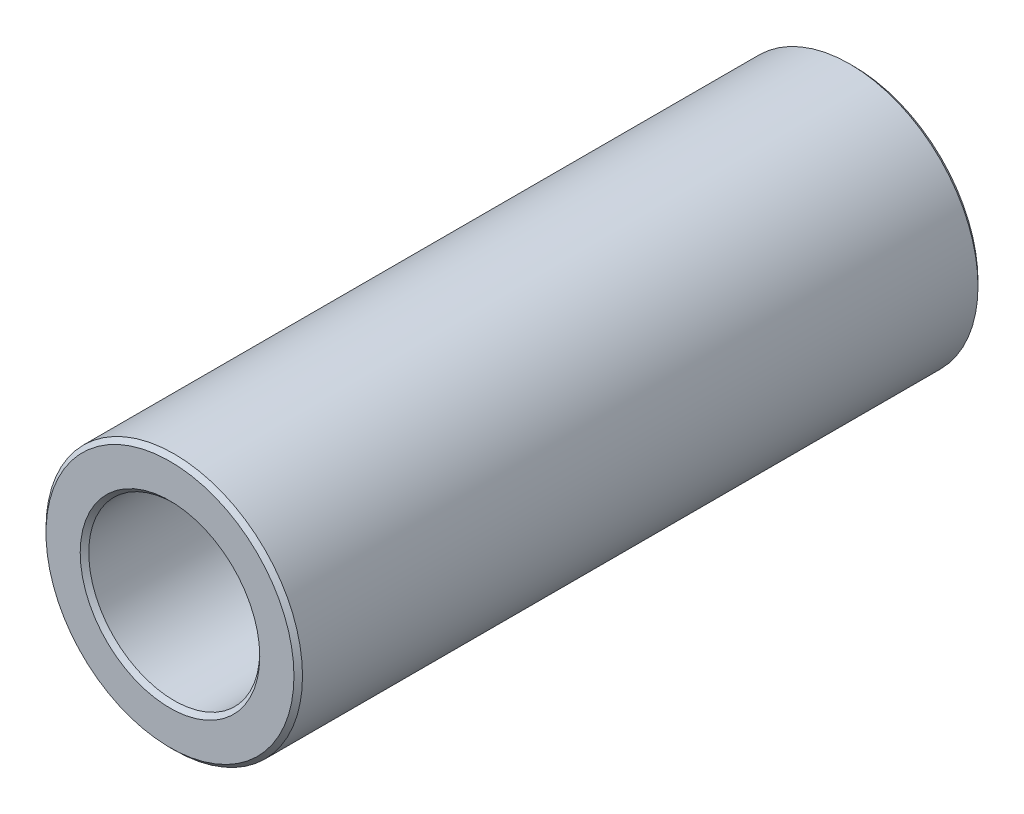
SolidWorks part; units mm, degrees
material "6061 Alloy"
ref_plane "Front Plane" through (0, 0, 0) normal (0, 0, 1) x (1, 0, 0)
ref_plane "Top Plane" through (0, 0, 0) normal (0, 1, 0) x (1, 0, 0)
ref_plane "Right Plane" through (0, 0, 0) normal (1, 0, 0) x (0, 0, -1)
sketch "Sketch1" plane through (0, 0, 0) normal (0, 0, 1) x (1, 0, 0)
  circle A0 centre (0, 0) radius 4.7625 construction
  circle A1 centre (0, 0) radius 3.175 construction
  point P4 (0, 4.7625)
  dimension "ID" = 6.35
  dimension "OD" = 9.525
sketch "Sketch2" plane through (0, 0, 0) normal (1, 0, 0) x (0, 0, -1)
  line L0 (-12.7, 4.7625) -> (12.7, 4.7625) construction
  dimension "Length" = 25.4
sketch "Sketch3" plane through (0, 0, 0) normal (0, 0, 1) x (1, 0, 0)
  circle A0 centre (0, 0) radius 3.175 construction
  circle A1 centre (0, 0) radius 4.7625 construction
  circle A2 centre (0, 0) radius 3.175
  circle A3 centre (0, 0) radius 4.7625
extrude "Boss-Extrude1" add sketch "Sketch3" against normal up to vertex (12.7 mm away) and the other way up to vertex (12.7 mm away) up to point (0, 4.7625, -12.7) other way up to point (0, 4.7625, 12.7)
chamfer "Chamfer1" distance 0.1588 angle 45 4 edges at (4.7625, 0, 12.7) (4.7625, 0, -12.7) (3.175, 0, 12.7) (3.175, 0, -12.7)
equation "\"D1@Chamfer1\"=(\"OD@Sketch1\"-\"ID@Sketch1\")*0.05"
